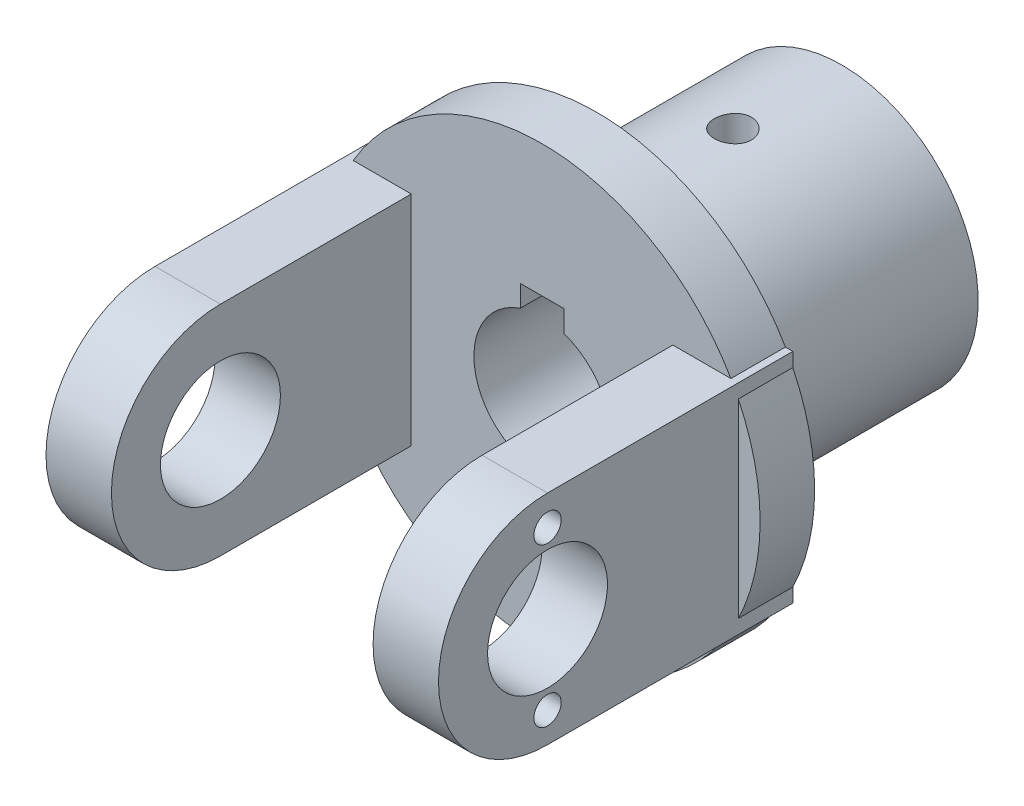
SolidWorks part; units mm, degrees
ref_plane "前视基准面" through (0, 0, 0) normal (0, 0, 1) x (1, 0, 0)
ref_plane "上视基准面" through (0, 0, 0) normal (0, 1, 0) x (1, 0, 0)
ref_plane "右视基准面" through (0, 0, 0) normal (1, 0, 0) x (0, 0, -1)
sketch "草图1" plane through (0, 0, 0) normal (0, 1, 0) x (1, 0, 0)
  line L0 (0, 0) -> (0, -55) construction
  line L1 (0, 0) -> (25, 0)
  line L2 (25, 0) -> (25, -45)
  line L3 (25, -45) -> (40, -45)
  line L4 (40, -45) -> (40, -55)
  line L5 (40, -55) -> (0, -55)
  line L6 (0, -55) -> (0, 0)
revolve "旋转1" add sketch "草图1" angle 360 about L0
ref_plane "基准面1" through (24, 0, 0) normal (1, 0, 0) x (0, 0, -1)
sketch "草图2" plane through (24, 0, 0) normal (1, 0, 0) x (0, 0, -1)
  line L0 (-45, -20) -> (-90, -20)
  line L1 (-90, 20) -> (-45, 20)
  line L2 (-45, 20) -> (-45, -20)
  arc A0 (-90, -20) -> (-90, 20) centre (-90, 0) cw
extrude "凸台-拉伸1" add sketch "草图2" along normal blind 12
mirror "镜向1" about plane through (0, 0, 0) normal (1, 0, 0) of "凸台-拉伸1"
sketch "草图3" plane through (0, 0, 0) normal (1, 0, 0) x (0, 0, -1)
  circle A0 centre (-90, 0) radius 11
extrude "切除-拉伸1" cut sketch "草图3" against normal mid plane 222
sketch "草图4" plane through (0, 0, 0) normal (0, 0, 1) x (1, 0, 0)
  circle A0 centre (0, 0) radius 12.5
extrude "切除-拉伸2" cut sketch "草图4" along normal through all
sketch "草图5" plane through (0, 0, 0) normal (0, 0, 1) x (1, 0, 0)
  line L0 (-4, 0) -> (4, 0)
  line L1 (4, 0) -> (4, 15.8)
  line L2 (4, 15.8) -> (-4, 15.8)
  line L3 (-4, 15.8) -> (-4, 0)
extrude "切除-拉伸3" cut sketch "草图5" along normal through all
ref_plane "基准面2" through (0, 25, 0) normal (0, 1, 0) x (1, 0, 0)
sketch "草图6" plane through (0, 25, 0) normal (0, 1, 0) x (1, 0, 0)
  circle A0 centre (0, -20) radius 3.4
extrude "切除-拉伸4" cut sketch "草图6" against normal blind 13
ref_plane "基准面3" through (36, 0, 0) normal (1, 0, 0) x (0, 0, -1)
sketch "草图7" plane through (36, 0, 0) normal (1, 0, 0) x (0, 0, -1)
  circle A0 centre (-90, 14.5) radius 2.5
  circle A1 centre (-90, -14.5) radius 2.5
extrude "切除-拉伸5" cut sketch "草图7" against normal blind 10
mirror "镜向2" about plane through (0, 0, 0) normal (1, 0, 0) of "切除-拉伸5"
